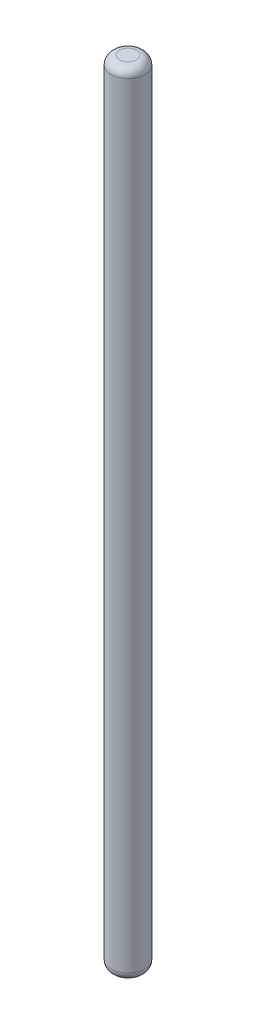
SolidWorks part; units mm, degrees
material "1023 Carbon Steel Sheet (SS)"
ref_plane "Front" through (0, 0, 0) normal (0, 0, 1) x (1, 0, 0)
ref_plane "Top" through (0, 0, 0) normal (0, 1, 0) x (1, 0, 0)
ref_plane "Right" through (0, 0, 0) normal (1, 0, 0) x (0, 0, -1)
sketch "Sketch1" plane through (0, 0, 0) normal (0, 1, 0) x (1, 0, 0)
  circle A0 centre (0, 0) radius 1
  dimension "D1" = 2
extrude "Boss-Extrude1" add sketch "Sketch1" along normal blind 47
fillet "Fillet1" radius 0.5 2 edges at (0, 0, 1) (0, 47, 1)
